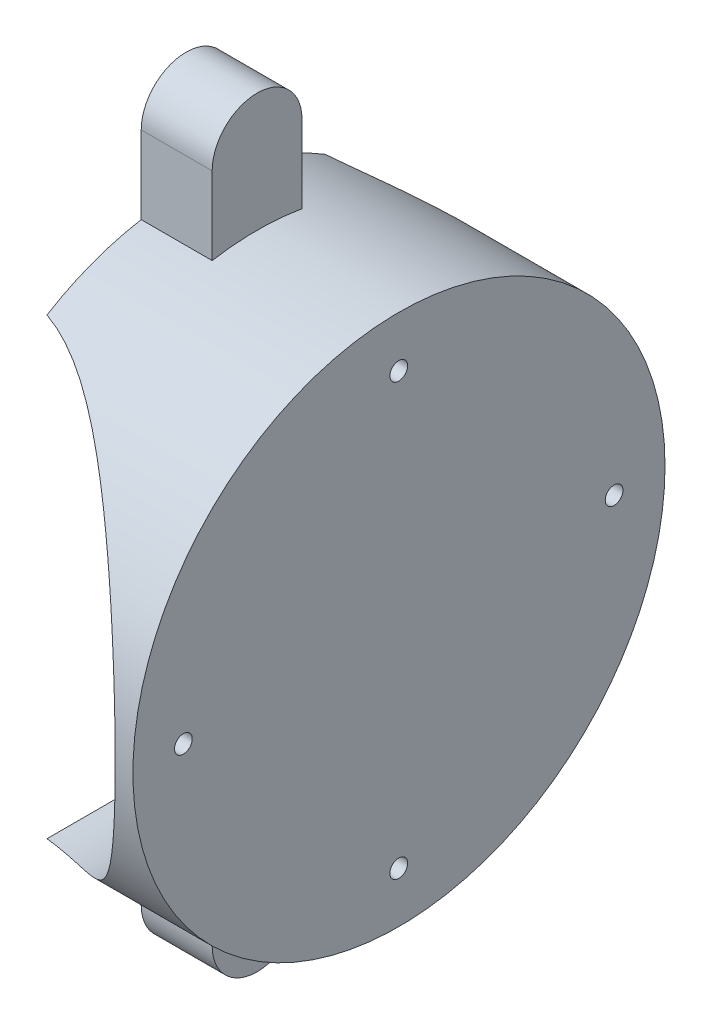
SolidWorks part; units mm, degrees
ref_plane "Front Plane" through (0, 0, 0) normal (0, 0, 1) x (1, 0, 0)
ref_plane "Top Plane" through (0, 0, 0) normal (0, 1, 0) x (1, 0, 0)
ref_plane "Right Plane" through (0, 0, 0) normal (1, 0, 0) x (0, 0, -1)
sketch "Sketch1" plane through (0, 0, 0) normal (1, 0, 0) x (0, 0, -1)
  circle A0 centre (0, 0) radius 75
  dimension "D1" = 150
extrude "Boss-Extrude1" add sketch "Sketch1" along normal blind 60 contours A0
sketch "Sketch5" plane through (0, 0, 0) normal (1, 0, 0) x (0, 0, -1)
  line L0 (0, 95.8279) -> (0, -93.3886) construction
  line L1 (12.6615, 95.8279) -> (12.6615, -93.3886)
  line L2 (-12.6615, 95.8279) -> (-12.6615, -93.3886)
  arc A0 (12.6615, 95.8279) -> (-12.6615, 95.8279) centre (0, 95.8279) ccw
  arc A1 (-12.6615, -93.3886) -> (12.6615, -93.3886) centre (0, -93.3886) ccw
  point P3 (0, 1.2197)
extrude "Boss-Extrude2" add sketch "Sketch5" along normal blind 20
sketch "Sketch6" plane through (0, 0, 0) normal (1, 0, 0) x (0, 0, -1)
  circle A0 centre (60.641, 0) radius 2.5
  point P2 (67.3171, 0)
  point P3 (60.641, 0)
  dimension "D1" = 5
extrude "Cut-Extrude4" cut sketch "Sketch6" along normal through all both and the other way through all contours A0
pattern_circular "CirPattern1" count 4 over 360 about axis through (0, 0, 0.0675) along (1, 0, 0) of "Cut-Extrude4"
sketch "Sketch3" plane through (0, 0, 0) normal (0, 0, 1) x (1, 0, 0)
  line L1 (0, 63.9235) -> (0, -63.9235)
  line L2 (0, 73.9235) -> (0, -73.9235) construction
  arc A1 (0, 63.9235) -> (0, -63.9235) centre (-9.6474, 0) cw
  point P3 (55, 0)
  point P4 (0, 0)
  point P5 (0, 0)
  point P6 (0, 73.9235)
  point P7 (0, 63.8079)
  point P10 (0, -73.9235)
  point P14 (0, -56.9178)
  dimension "D1" = 55
  dimension "D2" = 10
  dimension "D3" = 10
extrude "Cut-Extrude3" cut sketch "Sketch3" against normal through all both and the other way through all
